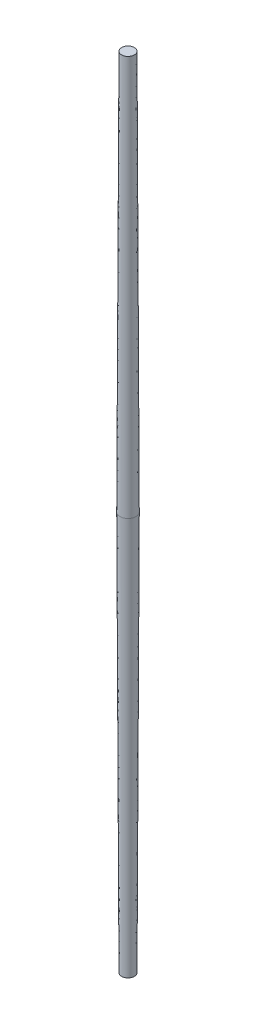
SolidWorks part; units mm, degrees
ref_plane "Plan de face" through (0, 0, 0) normal (0, 0, 1) x (1, 0, 0)
ref_plane "Plan de dessus" through (0, 0, 0) normal (0, 1, 0) x (1, 0, 0)
ref_plane "Plan de droite" through (0, 0, 0) normal (1, 0, 0) x (0, 0, -1)
sketch "Esquisse1" plane through (0, 0, 0) normal (0, 0, 1) x (1, 0, 0)
  line L0 (0, 0) -> (5, 0)
  line L1 (5, 0) -> (4, 250)
  line L2 (4, 250) -> (0, 250)
  line L3 (0, 250) -> (0, 0)
  dimension "D1" = 250
  dimension "D2" = 5
  dimension "D3" = 4
revolve "Révolution1" add sketch "Esquisse1" angle 360 about L3
mirror "Symétrie1" about plane through (0, 0, 0) normal (0, 1, 0) of "Révolution1"
scale "Echelle1" scale about centroid uniform scaling yes scale factor 1.5
